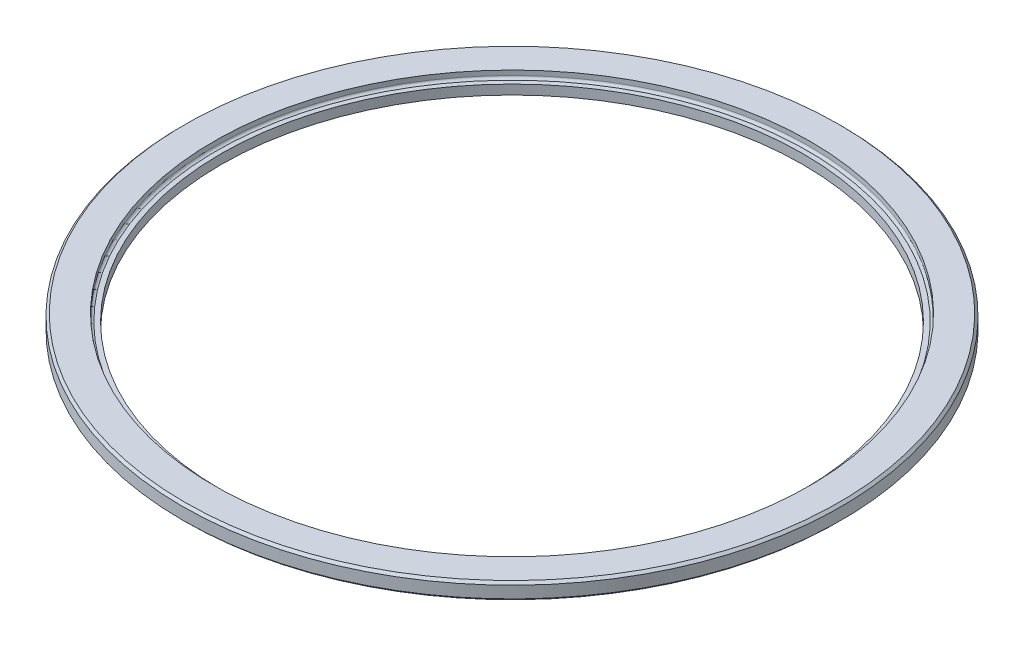
SolidWorks part; units mm, degrees
material "AISI 1045 Steel, cold drawn"
ref_plane "Front Plane" through (0, 0, 0) normal (0, 0, 1) x (1, 0, 0)
ref_plane "Top Plane" through (0, 0, 0) normal (0, 1, 0) x (1, 0, 0)
ref_plane "Right Plane" through (0, 0, 0) normal (1, 0, 0) x (0, 0, -1)
sketch "Primary Sketch" plane through (0, 0, 0) normal (0, 0, 1) x (1, 0, 0)
  line L0 (0, 0) -> (31.115, 0) construction
  line L1 (31.115, 0) -> (31.115, 1.016)
  line L2 (31.115, 1.016) -> (31.877, 1.016)
  line L3 (31.877, 1.016) -> (31.877, 1.778)
  line L4 (31.877, 1.778) -> (35.2425, 1.778)
  line L5 (35.2425, 1.778) -> (35.2425, 0)
  line L6 (35.2425, 0) -> (31.115, 0)
  line L7 (0, 0) -> (0, 4.8146) construction
  dimension "D1" = 0.762
  dimension "D2" = 1.016
  dimension "D3" = 1.778
  dimension "D4" = 31.115
  dimension "D5" = 35.2425
revolve "Primary Revolve" add sketch "Primary Sketch" angle 360 about L7
chamfer "Outer Chamfer" distance 0.254 angle 45 2 edges at (0, 0, -35.2425) (0, 1.778, -35.2425)
fillet "Inner Fillet" radius 0.254 1 edges at (0, 1.016, -31.877)
